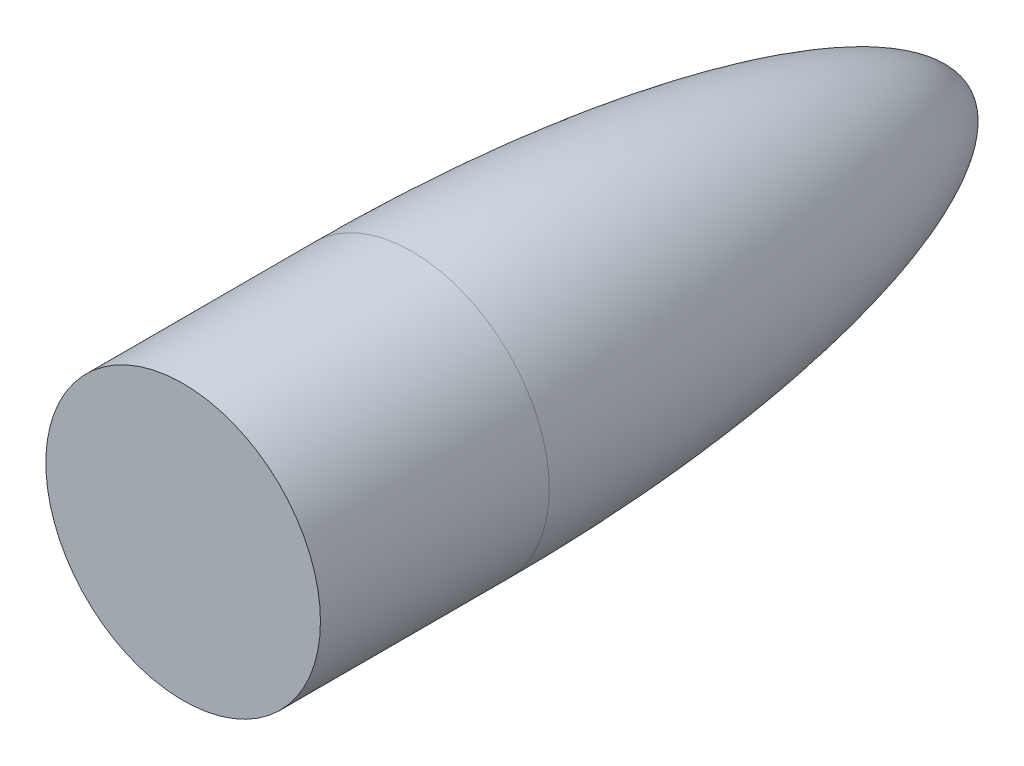
SolidWorks part; units mm, degrees
other "Markup1"
sketch "Sketch3" plane through (-76.2, 76.2, -762) normal (-0.6807, 0.6563, -0.3256) x (-0.115, 0.3432, 0.9322)
ref_plane "Front Plane" through (0, 0, 0) normal (0, 0, 1) x (1, 0, 0)
ref_plane "Top Plane" through (0, 0, 0) normal (0, 1, 0) x (1, 0, 0)
ref_plane "Right Plane"
sketch "Sketch1" plane through (0, 0, 0) normal (1, 0, 0) x (0, 0, -1)
  line L0 (0, 76.2) -> (0, 0)
  line L1 (0, 0) -> (304.8, 0)
  spline S0 degree 4 poles (-30.4804, 75.818) (-30.0025, 75.83) (-29.0488, 75.8534) (-27.1588, 75.8983) (-24.2668, 75.9595) (-20.9952, 76.0222) (-17.0886, 76.0818) (-13.4284, 76.1295) (-9.3736, 76.1653) (-5.9724, 76.1891) (-1.7308, 76.2003) (0.9674, 76.2011) (5.2762, 76.1918) (9.4524, 76.167) (14.7263, 76.1175) (20.5143, 76.0326) (26.4296, 75.9193) (32.27, 75.7774) (38.1541, 75.6069) (44.0104, 75.4074) (49.8819, 75.1789) (55.7424, 74.921) (61.6075, 74.6335) (67.4674, 74.3161) (73.3277, 73.9685) (79.1849, 73.5901) (85.0407, 73.1807) (92.3572, 72.6294) (101.1321, 71.9037) (111.3611, 70.961) (123.0381, 69.7462) (134.6991, 68.3874) (146.3416, 66.8769) (157.962, 65.2053) (169.5564, 63.3613) (181.1197, 61.3312) (192.6459, 59.0986) (206.9965, 56.0285) (224.1062, 51.8468) (241.4542, 46.7934) (258.457, 40.6597) (271.6074, 34.7742) (280.6678, 29.8995) (287.5932, 25.4001) (292.6256, 21.4625) (296.3049, 17.9902) (298.9686, 14.9494) (300.9102, 12.2477) (302.3257, 9.8055) (303.3479, 7.5586) (304.062, 5.4586) (304.5586, 3.3261) (304.7529, 1.711) (304.8, 0.6131) (304.8, 0) knots 0 0 0 0 0 0.005332 0.010664 0.021328 0.031991 0.042655 0.053319 0.063983 0.074647 0.08531 0.093524 0.101738 0.118165 0.134592 0.15102 0.167447 0.183874 0.200302 0.216729 0.233156 0.249584 0.266011 0.282438 0.298865 0.315293 0.33172 0.348147 0.381002 0.413857 0.446711 0.479566 0.512421 0.545275 0.57813 0.610984 0.643839 0.676694 0.742403 0.808112 0.845999 0.878853 0.903558 0.923169 0.938339 0.950287 0.960109 0.968354 0.975526 0.981836 0.987699 0.993143 1 1 1 1 1 construction
  spline S1 degree 4 poles (0, 76.2) (0.6711, 76.2) (2.0233, 76.1988) (5.2762, 76.1918) (9.4524, 76.167) (14.7263, 76.1175) (20.5143, 76.0326) (26.4296, 75.9193) (32.27, 75.7774) (38.1541, 75.6069) (44.0104, 75.4074) (49.8819, 75.1789) (55.7424, 74.921) (61.6075, 74.6335) (67.4674, 74.3161) (73.3277, 73.9685) (79.1849, 73.5901) (85.0407, 73.1807) (92.3572, 72.6294) (101.1321, 71.9037) (111.3611, 70.961) (123.0381, 69.7462) (134.6991, 68.3874) (146.3416, 66.8769) (157.962, 65.2053) (169.5564, 63.3613) (181.1197, 61.3312) (192.6459, 59.0986) (206.9965, 56.0285) (224.1062, 51.8468) (241.4542, 46.7934) (258.457, 40.6597) (271.6074, 34.7742) (280.6678, 29.8995) (287.5932, 25.4001) (292.6256, 21.4625) (296.3049, 17.9902) (298.9686, 14.9494) (300.9102, 12.2477) (302.3257, 9.8055) (303.3479, 7.5586) (304.062, 5.4586) (304.5586, 3.3261) (304.7529, 1.711) (304.8, 0.6131) (304.8, 0) knots 0.08531 0.08531 0.08531 0.08531 0.08531 0.093524 0.101738 0.118165 0.134592 0.15102 0.167447 0.183874 0.200302 0.216729 0.233156 0.249584 0.266011 0.282438 0.298865 0.315293 0.33172 0.348147 0.381002 0.413857 0.446711 0.479566 0.512421 0.545275 0.57813 0.610984 0.643839 0.676694 0.742403 0.808112 0.845999 0.878853 0.903558 0.923169 0.938339 0.950287 0.960109 0.968354 0.975526 0.981836 0.987699 0.993143 1 1 1 1 1
ref_axis "Axis1" through (0, 0, -480.06) along (0, 0, 1)
revolve "Revolve1" add sketch "Sketch1" angle 360 about axis through (0, 0, -480.06) along (0, 0, 1)
sketch "Sketch2" plane through (0, 0, 0) normal (0, 0, 1) x (1, 0, 0)
  circle A0 centre (0, 0) radius 76.2
  dimension "D1" = 152.4
extrude "Boss-Extrude1" add sketch "Sketch2" along normal blind 127
equation "\"BodyTubeRadius\"= 3in"
equation "\"ratio\"= 2"
equation "\"NoseConeLength\"= \"ratio\" * 2 * \"BodyTubeRadius\""
equation "\"D1@Sketch2\"=2*\"BodyTubeRadius\""
equation "\"BodyTubeLength\"=5"
